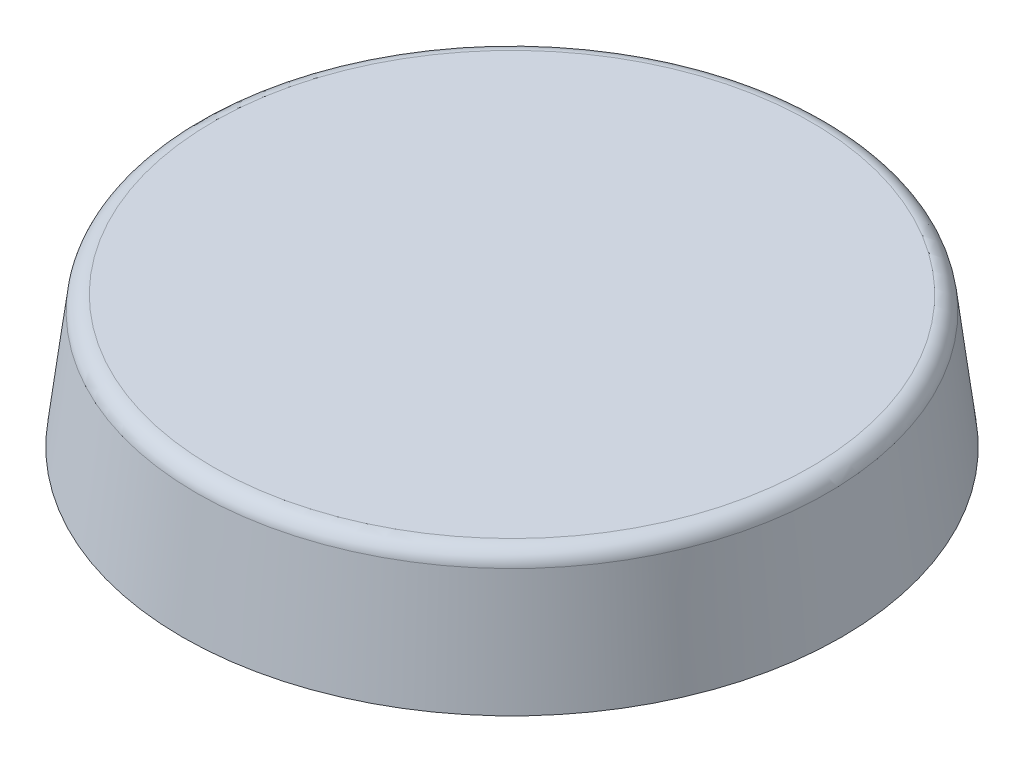
SolidWorks part; units mm, degrees
ref_plane "Piano frontale" through (0, 0, 0) normal (0, 0, 1) x (1, 0, 0)
ref_plane "Piano superiore" through (0, 0, 0) normal (0, 1, 0) x (1, 0, 0)
ref_plane "Piano destro" through (0, 0, 0) normal (1, 0, 0) x (0, 0, -1)
sketch "Schizzo1" plane through (0, 0, 0) normal (0, 1, 0) x (1, 0, 0)
  circle A0 centre (0, 0) radius 10
  dimension "D1" = 20
extrude "Estrusione-Estrusione1" add sketch "Schizzo1" along normal blind 4 draft 7
fillet "Raccordo1" radius 0.5 1 edges at (0, 4, 9.5089)
